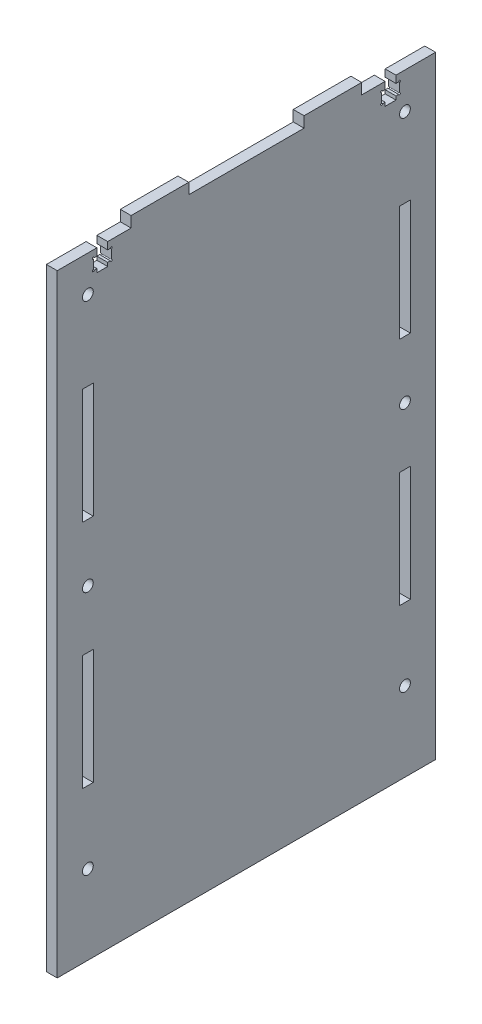
SolidWorks part; units mm, degrees
ref_plane "Front" through (0, 0, 0) normal (0, 0, 1) x (1, 0, 0)
ref_plane "Top" through (0, 0, 0) normal (0, 1, 0) x (1, 0, 0)
ref_plane "Right" through (0, 0, 0) normal (1, 0, 0) x (0, 0, -1)
sketch "Croquis1" plane through (0, 0, 0) normal (1, 0, 0) x (0, 0, -1)
  line L0 (52.5, 85) -> (52.5, 166.2941) construction
  line L1 (0, 0) -> (105, 0)
  line L2 (0, 0) -> (0, 170)
  line L3 (0, 170) -> (105, 170)
  line L4 (105, 0) -> (105, 170)
  line L5 (0, 0) -> (105, 170) construction
  line L6 (0, 170) -> (105, 0) construction
  line L7 (52.5, 166.2941) -> (95, 166.2941) construction
  line L8 (95, 166.2941) -> (95, 138) construction
  line L9 (95, 74) -> (98, 74)
  line L10 (95, 138) -> (98, 138)
  line L11 (95, 138) -> (95, 106)
  line L12 (95, 106) -> (98, 106)
  line L13 (98, 138) -> (98, 106)
  line L14 (95, 138) -> (98, 106) construction
  line L15 (95, 106) -> (98, 138) construction
  line L16 (95, 74) -> (95, 42)
  line L17 (95, 42) -> (98, 42)
  line L18 (98, 74) -> (98, 42)
  line L19 (95, 74) -> (98, 42) construction
  line L20 (95, 42) -> (98, 74) construction
  line L21 (10, 42) -> (7, 74) construction
  line L22 (10, 74) -> (7, 42) construction
  line L23 (10, 106) -> (7, 138) construction
  line L24 (10, 138) -> (7, 106) construction
  line L25 (7, 74) -> (7, 42)
  line L26 (10, 42) -> (7, 42)
  line L27 (10, 74) -> (10, 42)
  line L28 (7, 138) -> (7, 106)
  line L29 (10, 106) -> (7, 106)
  line L30 (10, 138) -> (10, 106)
  line L31 (10, 138) -> (7, 138)
  line L32 (10, 74) -> (7, 74)
  line L33 (186.0661, 90.8615) -> (175.8771, 68.8248) construction
  line L34 (175.8771, 68.8248) -> (174.4554, 68.8248) construction
  line L35 (96.5, 106) -> (96.5, 74) construction
  line L36 (96.5, 42) -> (96.5, 22) construction
  circle A0 centre (96.5, 160) radius 1.5
  circle A1 centre (96.5, 22) radius 1.5
  circle A2 centre (96.5, 90) radius 1.5
  circle A3 centre (8.5, 22) radius 1.5
  circle A4 centre (8.5, 90) radius 1.5
  circle A5 centre (8.5, 160) radius 1.5
  point P4 (52.5, 85)
  point P13 (96.5, 122)
  point P19 (96.5, 58)
  point P27 (8.5, 58)
  point P28 (8.5, 122)
  dimension "D8" = 3
  dimension "D10" = 3
  dimension "D11" = 3
  dimension "D1" = 105
  dimension "D2" = 170
  dimension "D3" = 42.5
  dimension "D4" = 3
  dimension "D5" = 32
  dimension "D6" = 32
  dimension "D9" = 10
  dimension "D12" = 20
  dimension "D7" = 2
extrude "Saliente-Extruir1" add sketch "Croquis1" along normal blind 3
sketch "Croquis2" plane through (0, 170, 0) normal (0, 1, 0) x (1, 0, 0)
  line L0 (0, 52.5) -> (3, 52.5) construction
  line L1 (0, 105) -> (0, 0) construction
  line L2 (3, 105) -> (3, 0) construction
  line L3 (0, 20.5) -> (3, 36.5) construction
  line L4 (0, 68.5) -> (3, 68.5)
  line L5 (0, 68.5) -> (0, 84.5)
  line L6 (0, 84.5) -> (3, 84.5)
  line L7 (3, 68.5) -> (3, 84.5)
  line L8 (0, 68.5) -> (3, 84.5) construction
  line L9 (0, 84.5) -> (3, 68.5) construction
  line L10 (0, 36.5) -> (3, 20.5) construction
  line L11 (3, 36.5) -> (3, 20.5)
  line L12 (0, 20.5) -> (3, 20.5)
  line L13 (0, 36.5) -> (0, 20.5)
  line L14 (0, 36.5) -> (3, 36.5)
  point P10 (1.5, 76.5)
  point P15 (1.5, 28.5)
  dimension "D1" = 16
  dimension "D2" = 16
extrude "Saliente-Extruir2" add sketch "Croquis2" along normal blind 3
sketch "Croquis3" plane through (0, 0, 0) normal (-1, 0, 0) x (0, 0, 1)
  line L0 (-91, 170) -> (-91, 168)
  line L1 (-91, 168) -> (-90.25, 168)
  line L2 (-90, 167.75) -> (-90, 165.25)
  line L3 (-90.25, 165) -> (-91, 165)
  line L4 (-91, 165) -> (-91, 164)
  line L5 (-91, 164) -> (-94, 164)
  line L6 (-92.5, 164.0999) -> (-92.5, 170) construction
  line L7 (-94, 165) -> (-94, 164)
  line L8 (-94.75, 165) -> (-94, 165)
  line L9 (-95, 167.75) -> (-95, 165.25)
  line L10 (-94, 168) -> (-94.75, 168)
  line L11 (-94, 170) -> (-94, 168)
  line L12 (-76.5, 173) -> (-76.5, 170) construction
  line L13 (-84.5, 173) -> (-68.5, 173) construction
  line L14 (-76.5, 170) -> (-92.5, 170) construction
  line L15 (-105, 170) -> (-84.5, 170) construction
  line L16 (-52.5, 170) -> (-52.5, 0) construction
  line L17 (-68.5, 170) -> (-36.5, 170) construction
  line L18 (0, 0) -> (-105, 0) construction
  line L19 (-28.5, 170) -> (-12.5, 170) construction
  line L20 (-28.5, 173) -> (-28.5, 170) construction
  line L21 (-12.5, 164.0999) -> (-12.5, 170) construction
  line L22 (-11, 170) -> (-11, 168)
  line L23 (-11, 168) -> (-10.25, 168)
  line L24 (-10, 167.75) -> (-10, 165.25)
  line L25 (-10.25, 165) -> (-11, 165)
  line L26 (-11, 165) -> (-11, 164)
  line L27 (-14, 164) -> (-11, 164)
  line L28 (-14, 165) -> (-14, 164)
  line L29 (-14.75, 165) -> (-14, 165)
  line L30 (-15, 167.75) -> (-15, 165.25)
  line L31 (-14, 168) -> (-14.75, 168)
  line L32 (-14, 170) -> (-14, 168)
  arc A0 (-90.25, 165) -> (-90, 165.25) centre (-90, 165) ccw
  arc A1 (-90, 167.75) -> (-90.25, 168) centre (-90, 168) ccw
  arc A2 (-95, 167.75) -> (-94.75, 168) centre (-95, 168) cw
  arc A3 (-94.75, 165) -> (-95, 165.25) centre (-95, 165) cw
  arc A4 (-10.25, 165) -> (-10, 165.25) centre (-10, 165) ccw
  arc A5 (-10, 167.75) -> (-10.25, 168) centre (-10, 168) ccw
  arc A6 (-15, 167.75) -> (-14.75, 168) centre (-15, 168) cw
  arc A7 (-14.75, 165) -> (-15, 165.25) centre (-15, 165) cw
  point P3 (-92.5, 164)
  point P60 (-12.5, 164)
  line M7 (0, 170) -> (-20.5, 170)
  line M15 (-84.5, 170) -> (-105, 170)
  dimension "D4" = 0.5
  dimension "D5" = 0.5
  dimension "D1" = 2
  dimension "D2" = 1.5
  dimension "D3" = 2.5
  dimension "D6" = 3
  dimension "D7" = 1
  dimension "D8" = 16
extrude "Cortar-Extruir1" cut sketch "Croquis3" against normal blind 3 contours A7 L29 L28 L27 L26 L25 A4 L24 A5 L23 L22 L32 L31 A6 L30 M7 | A3 L8 L7 L5 L4 L3 A0 L2 A1 L1 L0 L11 L10 A2 L9 M15
